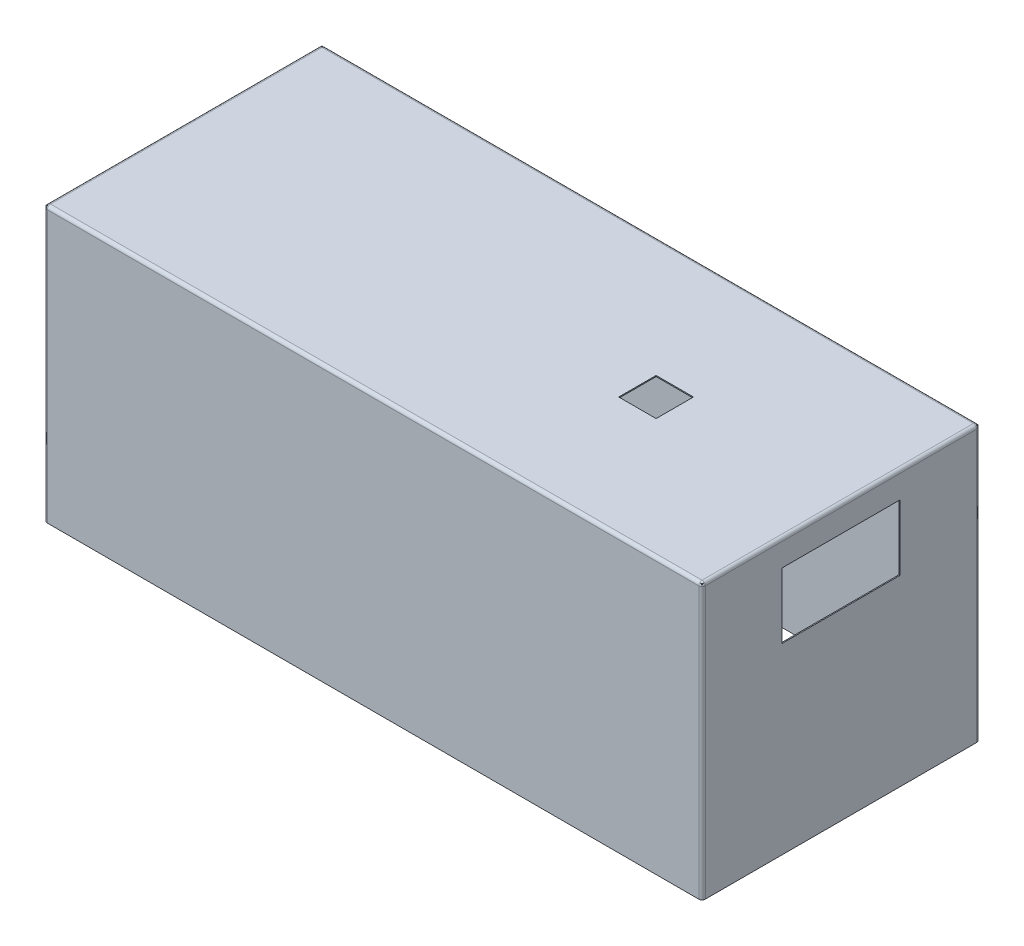
SolidWorks part; units mm, degrees
material "Alumina"
ref_plane "Front Plane" through (0, 0, 0) normal (0, 0, 1) x (1, 0, 0)
ref_plane "Top Plane" through (0, 0, 0) normal (0, 1, 0) x (1, 0, 0)
ref_plane "Right Plane" through (0, 0, 0) normal (1, 0, 0) x (0, 0, -1)
sketch "Sketch2" plane through (0, 0, 0) normal (0, 1, 0) x (1, 0, 0)
  line L1 (-503.1, 212.5) -> (503.1, 212.5)
  line L2 (-503.1, 212.5) -> (-503.1, -212.5)
  line L3 (-503.1, -212.5) -> (503.1, -212.5)
  line L4 (503.1, 212.5) -> (503.1, -212.5)
  line L5 (-503.1, 212.5) -> (503.1, -212.5) construction
  line L6 (-503.1, -212.5) -> (503.1, 212.5) construction
  line L7 (-501.5125, 210.9125) -> (501.5125, 210.9125)
  line L8 (-501.5125, 210.9125) -> (-501.5125, -210.9125)
  line L9 (-501.5125, -210.9125) -> (501.5125, -210.9125)
  line L10 (501.5125, 210.9125) -> (501.5125, -210.9125)
  line L11 (-501.5125, 210.9125) -> (501.5125, -210.9125) construction
  line L12 (-501.5125, -210.9125) -> (501.5125, 210.9125) construction
  point P0 (0, 0)
  point P6 (0, 0)
  dimension "D1" = 1006.2
  dimension "D2" = 425
  dimension "D3" = 1003.025
  dimension "D4" = 421.825
extrude "Boss-Extrude1" add sketch "Sketch2" along normal blind 420
sketch "Sketch3" plane through (0, 0, 0) normal (0, 1, 0) x (1, 0, 0)
  line L1 (-503.1, 212.5) -> (503.1, 212.5)
  line L2 (-503.1, 212.5) -> (-503.1, -212.5)
  line L3 (-503.1, -212.5) -> (503.1, -212.5)
  line L4 (503.1, 212.5) -> (503.1, -212.5)
  line L5 (-503.1, 212.5) -> (503.1, -212.5) construction
  line L6 (-503.1, -212.5) -> (503.1, 212.5) construction
  point P0 (0, 0)
  dimension "D1" = 1006.2
  dimension "D2" = 425
extrude "Boss-Extrude2" add sketch "Sketch3" against normal blind 1.5875 from offset 420
fillet "Fillet2" radius 5 8 edges at (0, 420, 212.5) (-503.1, 420, 0) (0, 420, -212.5) (503.1, 420, 0) (503.1, 210, 212.5) (-503.1, 210, 212.5) (-503.1, 210, -212.5) (503.1, 210, -212.5)
sketch "Sketch4" plane through (-503.1, 0, 0) normal (-1, 0, 0) x (0, 0, 1)
  line L0 (-207.5, 0) -> (207.5, 0) construction
  line L1 (-40, 0) -> (40, 0)
  line L2 (-40, 0) -> (-40, 80)
  line L3 (-40, 80) -> (40, 80)
  line L4 (40, 0) -> (40, 80)
  line L5 (-40, 0) -> (40, 80) construction
  line L6 (-40, 80) -> (40, 0) construction
  point P4 (0, 40)
  dimension "D1" = 80
  dimension "D2" = 80
extrude "Cut-Extrude1" cut sketch "Sketch4" against normal up to next
sketch "Sketch5" plane through (0, 0, 212.5) normal (0, 0, 1) x (1, 0, 0)
  line L0 (102.4542, 1871.2645) -> (102.4542, 2121.2645) construction
  dimension "D1" = 250
sketch "Sketch6" plane through (0, 0, -212.5) normal (0, 0, -1) x (-1, 0, 0)
  line L0 (-163.7052, 31.2035) -> (-163.7052, 281.2035) construction
  dimension "D1" = 250
sketch "Sketch7" plane through (0, 0, 0) normal (0, 1, 0) x (1, 0, 0)
  line L0 (-231, 0) -> (231, 0) construction
  line L1 (191.825, 28.575) -> (248.975, 28.575)
  line L2 (191.825, 28.575) -> (191.825, -28.575)
  line L3 (191.825, -28.575) -> (248.975, -28.575)
  line L4 (248.975, 28.575) -> (248.975, -28.575)
  line L5 (191.825, 28.575) -> (248.975, -28.575) construction
  line L6 (191.825, -28.575) -> (248.975, 28.575) construction
  point P0 (220.4, 0)
  dimension "D1" = 57.15
  dimension "D2" = 220.4
extrude "Cut-Extrude2" cut sketch "Sketch7" along normal up to surface (420 mm away) up to face at (0, 420, 0)
sketch "Sketch8" plane through (0, 0, 0) normal (1, 0, 0) x (0, 0, -1)
  line L0 (0, 231) -> (0, -231) construction
  line L1 (-90, 380) -> (90, 380)
  line L2 (-90, 380) -> (-90, 280)
  line L3 (-90, 280) -> (90, 280)
  line L4 (90, 380) -> (90, 280)
  line L5 (-90, 380) -> (90, 280) construction
  line L6 (-90, 280) -> (90, 380) construction
  line L7 (233.75, 0) -> (-233.75, 0) construction
  point P0 (0, 330)
  dimension "D1" = 330
  dimension "D2" = 180
  dimension "D3" = 100
extrude "Cut-Extrude3" cut sketch "Sketch8" along normal up to surface (503.1 mm away) up to face at (503.1, 207.5, 0)
sketch "Sketch9" plane through (0, 0, 0) normal (1, 0, 0) x (0, 0, -1)
  line L0 (0, 231) -> (0, -231) construction
  line L1 (90, 180) -> (-90, 180)
  line L2 (90, 180) -> (90, 80)
  line L3 (90, 80) -> (-90, 80)
  line L4 (-90, 180) -> (-90, 80)
  line L5 (90, 180) -> (-90, 80) construction
  line L6 (90, 80) -> (-90, 180) construction
  line L7 (233.75, 0) -> (-233.75, 0) construction
  point P0 (0, 130)
  dimension "D1" = 180
  dimension "D2" = 100
  dimension "D3" = 130
extrude "Cut-Extrude4" cut sketch "Sketch9" against normal up to surface (503.1 mm away) up to face at (-503.1, 123.75, 0)
equation "\"sheetMetalThickness\"= 1in / 16"
equation "\"shellLength\"= 930mm + 3in"
equation "\"shellWidth\"= 425mm"
equation "\"shellHeight\"= 420mm"
equation "\"D1@Sketch2\"=\"shellLength\""
equation "\"D2@Sketch2\"=\"shellWidth\""
equation "\"D3@Sketch2\"=\"shellLength\"-\"sheetMetalThickness\"*2"
equation "\"D4@Sketch2\"=\"shellWidth\"-\"sheetMetalThickness\"*2"
equation "\"D1@Boss-Extrude1\"=\"shellHeight\""
equation "\"D1@Sketch3\"=\"shellLength\""
equation "\"D2@Sketch3\"=\"shellWidth\""
equation "\"D19@Boss-Extrude2\"=\"shellHeight\""
equation "\"D1@Boss-Extrude2\"=\"sheetMetalThickness\""
equation "\"D2@Sketch7\"=\"shellLength\"/2 -282.7"
equation "\"D1@Sketch8\"=\"shellHeight\"-90"
